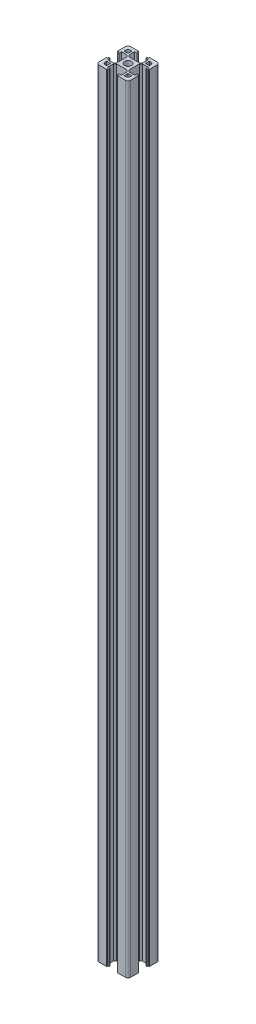
SolidWorks part; units mm, degrees
material "氧化铝"
ref_plane "前视基准面" through (0, 0, 0) normal (0, 0, 1) x (1, 0, 0)
ref_plane "上视基准面" through (0, 0, 0) normal (0, 1, 0) x (1, 0, 0)
ref_plane "右视基准面" through (0, 0, 0) normal (1, 0, 0) x (0, 0, -1)
sketch "草图1" plane through (0, 0, 0) normal (0, 1, 0) x (1, 0, 0)
  line L0 (-1000, 0) -> (49000, 0) construction
  line L1 (0, -1000) -> (0, 49000) construction
  line L2 (-12.8, 4.1) -> (-12.8, 6.4956)
  line L3 (-12.8, 6.4956) -> (-7.2734, 6.4956)
  line L4 (-7.2734, 6.4956) -> (-5.8, 5.0222)
  line L5 (-5.8, 5.0222) -> (-5.8, 0)
  line L6 (-12.8, 4.1) -> (-14, 4.1)
  line L7 (-14, 4.1) -> (-14, 5.2)
  line L8 (-14, 5.2) -> (-15, 5.2)
  line L9 (-15, 5.2) -> (-15, 12.5)
  line L10 (-12, 9.5) -> (-12, 8.25)
  line L11 (-12, 8.25) -> (-8.25, 8.25)
  line L12 (707.1068, -707.1068) -> (-34648.2323, 34648.2323) construction
  line L13 (-8.25, 12) -> (-8.25, 8.25)
  line L14 (-9.5, 12) -> (-8.25, 12)
  line L15 (-5.2, 15) -> (-12.5, 15)
  line L16 (-5.2, 14) -> (-5.2, 15)
  line L17 (-4.1, 14) -> (-5.2, 14)
  line L18 (-4.1, 12.8) -> (-4.1, 14)
  line L19 (-5.0222, 5.8) -> (0, 5.8)
  line L20 (-6.4956, 7.2734) -> (-5.0222, 5.8)
  line L21 (-6.4956, 12.8) -> (-6.4956, 7.2734)
  line L22 (-4.1, 12.8) -> (-6.4956, 12.8)
  line L23 (4.1, 12.8) -> (6.4956, 12.8)
  line L24 (6.4956, 12.8) -> (6.4956, 7.2734)
  line L25 (6.4956, 7.2734) -> (5.0222, 5.8)
  line L26 (5.0222, 5.8) -> (0, 5.8)
  line L27 (4.1, 12.8) -> (4.1, 14)
  line L28 (4.1, 14) -> (5.2, 14)
  line L29 (5.2, 14) -> (5.2, 15)
  line L30 (5.2, 15) -> (12.5, 15)
  line L31 (9.5, 12) -> (8.25, 12)
  line L32 (8.25, 12) -> (8.25, 8.25)
  line L33 (12, 8.25) -> (8.25, 8.25)
  line L34 (12, 9.5) -> (12, 8.25)
  line L35 (15, 5.2) -> (15, 12.5)
  line L36 (14, 5.2) -> (15, 5.2)
  line L37 (14, 4.1) -> (14, 5.2)
  line L38 (12.8, 4.1) -> (14, 4.1)
  line L39 (5.8, 5.0222) -> (5.8, 0)
  line L40 (7.2734, 6.4956) -> (5.8, 5.0222)
  line L41 (12.8, 6.4956) -> (7.2734, 6.4956)
  line L42 (12.8, 4.1) -> (12.8, 6.4956)
  line L43 (12.8, -4.1) -> (12.8, -6.4956)
  line L44 (12.8, -6.4956) -> (7.2734, -6.4956)
  line L45 (7.2734, -6.4956) -> (5.8, -5.0222)
  line L46 (5.8, -5.0222) -> (5.8, 0)
  line L47 (12.8, -4.1) -> (14, -4.1)
  line L48 (14, -4.1) -> (14, -5.2)
  line L49 (14, -5.2) -> (15, -5.2)
  line L50 (15, -5.2) -> (15, -12.5)
  line L51 (12, -9.5) -> (12, -8.25)
  line L52 (12, -8.25) -> (8.25, -8.25)
  line L53 (8.25, -12) -> (8.25, -8.25)
  line L54 (9.5, -12) -> (8.25, -12)
  line L55 (5.2, -15) -> (12.5, -15)
  line L56 (5.2, -14) -> (5.2, -15)
  line L57 (4.1, -14) -> (5.2, -14)
  line L58 (4.1, -12.8) -> (4.1, -14)
  line L59 (5.0222, -5.8) -> (0, -5.8)
  line L60 (6.4956, -7.2734) -> (5.0222, -5.8)
  line L61 (6.4956, -12.8) -> (6.4956, -7.2734)
  line L62 (4.1, -12.8) -> (6.4956, -12.8)
  line L63 (-4.1, -12.8) -> (-6.4956, -12.8)
  line L64 (-6.4956, -12.8) -> (-6.4956, -7.2734)
  line L65 (-6.4956, -7.2734) -> (-5.0222, -5.8)
  line L66 (-5.0222, -5.8) -> (0, -5.8)
  line L67 (-4.1, -12.8) -> (-4.1, -14)
  line L68 (-4.1, -14) -> (-5.2, -14)
  line L69 (-5.2, -14) -> (-5.2, -15)
  line L70 (-5.2, -15) -> (-12.5, -15)
  line L71 (-9.5, -12) -> (-8.25, -12)
  line L72 (-8.25, -12) -> (-8.25, -8.25)
  line L73 (-12, -8.25) -> (-8.25, -8.25)
  line L74 (-12, -9.5) -> (-12, -8.25)
  line L75 (-15, -5.2) -> (-15, -12.5)
  line L76 (-14, -5.2) -> (-15, -5.2)
  line L77 (-14, -4.1) -> (-14, -5.2)
  line L78 (-12.8, -4.1) -> (-14, -4.1)
  line L79 (-5.8, -5.0222) -> (-5.8, 0)
  line L80 (-7.2734, -6.4956) -> (-5.8, -5.0222)
  line L81 (-12.8, -6.4956) -> (-7.2734, -6.4956)
  line L82 (-12.8, -4.1) -> (-12.8, -6.4956)
  circle A0 centre (0, 0) radius 3.4
  arc A1 (-12, 9.5) -> (-9.5, 12) centre (-9.5, 9.5) cw
  arc A2 (-15, 12.5) -> (-12.5, 15) centre (-12.5, 12.5) cw
  arc A3 (9.5, 12) -> (12, 9.5) centre (9.5, 9.5) cw
  arc A4 (12.5, 15) -> (15, 12.5) centre (12.5, 12.5) cw
  arc A5 (12, -9.5) -> (9.5, -12) centre (9.5, -9.5) cw
  arc A6 (15, -12.5) -> (12.5, -15) centre (12.5, -12.5) cw
  arc A7 (-9.5, -12) -> (-12, -9.5) centre (-9.5, -9.5) cw
  arc A8 (-12.5, -15) -> (-15, -12.5) centre (-12.5, -12.5) cw
  point P32 (-12, 12)
  point P35 (-15, 15)
  point P114 (0, 0)
  dimension "D1" = 6.8
  dimension "D12" = 2.5
  dimension "D2" = 15
  dimension "D3" = 1.1
  dimension "D4" = 9.2
  dimension "D5" = 4.1
  dimension "D6" = 45
  dimension "D7" = 5.2
  dimension "D8" = 1
  dimension "D9" = 2.2
  dimension "D10" = 3.75
  dimension "D11" = 8.25
  dimension "D13" = 4
extrude "凸台-拉伸1" add sketch "草图1" along normal blind 735
